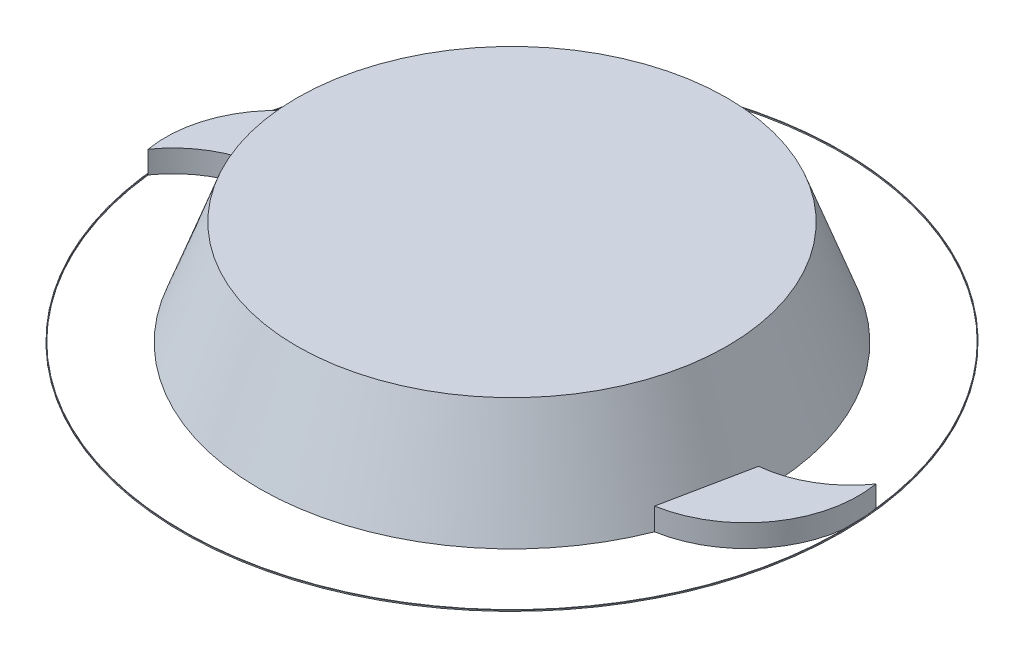
SolidWorks part; units mm, degrees
ref_plane "Front Plane" through (0, 0, 0) normal (0, 0, 1) x (1, 0, 0)
ref_plane "Top Plane" through (0, 0, 0) normal (0, 1, 0) x (1, 0, 0)
ref_plane "Right Plane" through (0, 0, 0) normal (1, 0, 0) x (0, 0, -1)
sketch "Sketch1" plane through (0, 0, 0) normal (0, 1, 0) x (1, 0, 0)
  circle A0 centre (0, 0) radius 215.9
  dimension "D1" = 431.8
extrude "Boss-Extrude1" add sketch "Sketch1" along normal blind 88.9 draft 20
sketch "Sketch2" plane through (0, 0, 0) normal (0, -1, 0) x (1, 0, 0)
  line L0 (-215.8313, -5.4477) -> (-200.854, -79.1863)
  arc A0 (-215.8313, -5.4477) -> (-278.9344, 31.5122) centre (-206.7294, 82.4415) cw
  circle A1 centre (0, 0) radius 215.9 construction
  arc A2 (-278.9344, 31.5122) -> (-200.854, -79.1863) centre (-184.5449, 15.2031) ccw
  circle A3 centre (0, 0) radius 280.7088 construction
extrude "Boss-Extrude2" add sketch "Sketch2" against normal blind 19.05
pattern_circular "CirPattern1" count 2 over 360 about axis through (0, 0, 0) along (0, 1, 0) of "Boss-Extrude2"
sketch "Sketch3" plane through (0, 0, 0) normal (0, -1, 0) x (1, 0, 0)
  circle A0 centre (0, 0) radius 280.7088
extrude "Extrude-Thin1" add sketch "Sketch3" against normal blind 1 thin
